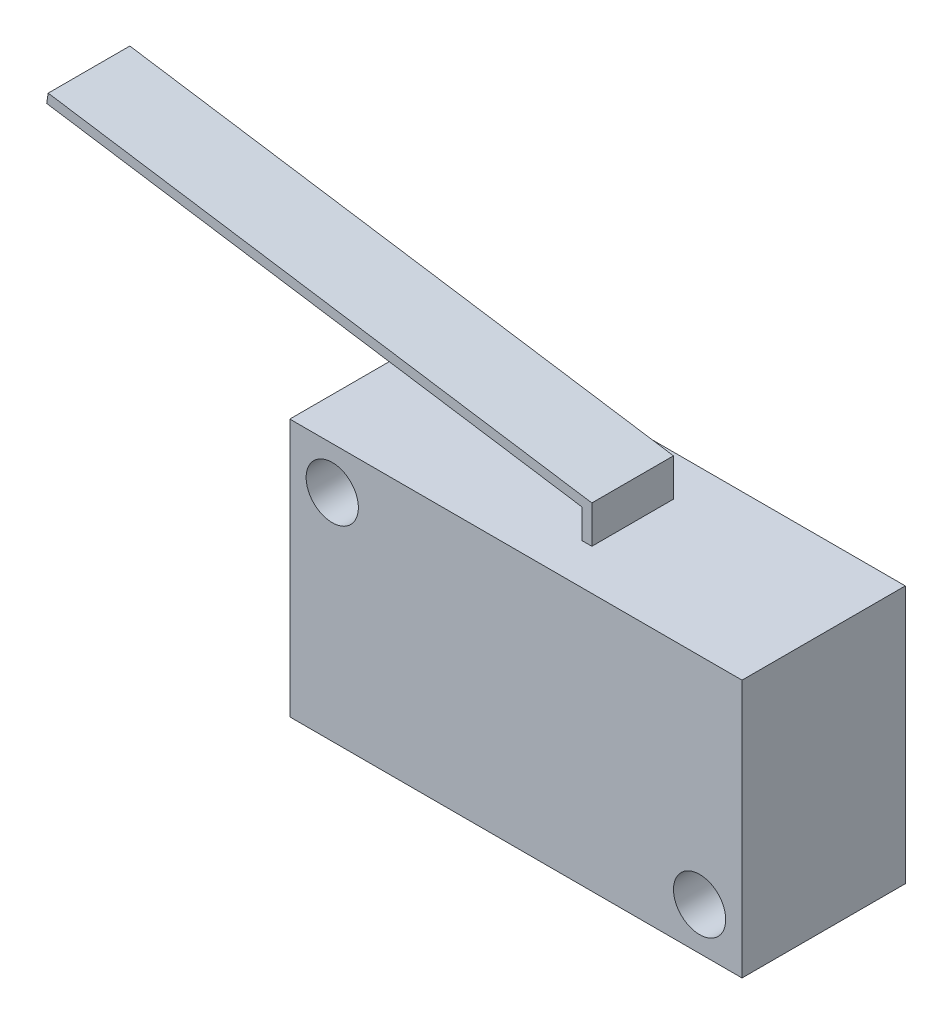
SolidWorks part; units mm, degrees
ref_plane "正面" through (0, 0, 0) normal (0, 0, 1) x (1, 0, 0)
ref_plane "平面" through (0, 0, 0) normal (0, 1, 0) x (1, 0, 0)
ref_plane "右側面" through (0, 0, 0) normal (1, 0, 0) x (0, 0, -1)
sketch "ｽｹｯﾁ1" plane through (0, 0, 0) normal (0, 0, 1) x (1, 0, 0)
  line L1 (13.85, -7.9) -> (-13.85, -7.9)
  line L2 (13.85, -7.9) -> (13.85, 7.9)
  line L3 (13.85, 7.9) -> (-13.85, 7.9)
  line L4 (-13.85, -7.9) -> (-13.85, 7.9)
  line L5 (13.85, -7.9) -> (-13.85, 7.9) construction
  line L6 (13.85, 7.9) -> (-13.85, -7.9) construction
  circle A0 centre (-11.25, 5.3) radius 1.6
  circle A1 centre (11.25, -5.3) radius 1.6
  point P0 (0, 0)
  dimension "D3" = 3.2
  dimension "D5" = 2.6
  dimension "D6" = 2.6
  dimension "D7" = 2.6
  dimension "D1" = 27.7
  dimension "D2" = 15.8
  dimension "D4" = 2.6
extrude "ﾎﾞｽ - 押し出し1" add sketch "ｽｹｯﾁ1" along normal mid plane 10
sketch "ｽｹｯﾁ2" plane through (0, 0, 0) normal (0, 0, 1) x (1, 0, 0)
  line L0 (2.15, 7.9) -> (2.15, 10.2)
  line L1 (13.85, 7.9) -> (-13.85, 7.9) construction
  line L2 (2.15, 10.2) -> (-31.15, 15.2887)
  line L3 (13.85, -7.9) -> (13.85, 7.9) construction
  dimension "D1" = 98.688
  dimension "D2" = 2.3
  dimension "D3" = 11.7
  dimension "D4" = 45
extrude "押し出し-薄板1" add sketch "ｽｹｯﾁ2" along normal mid plane 5 thin thin type one direction reverse wall 0.6
